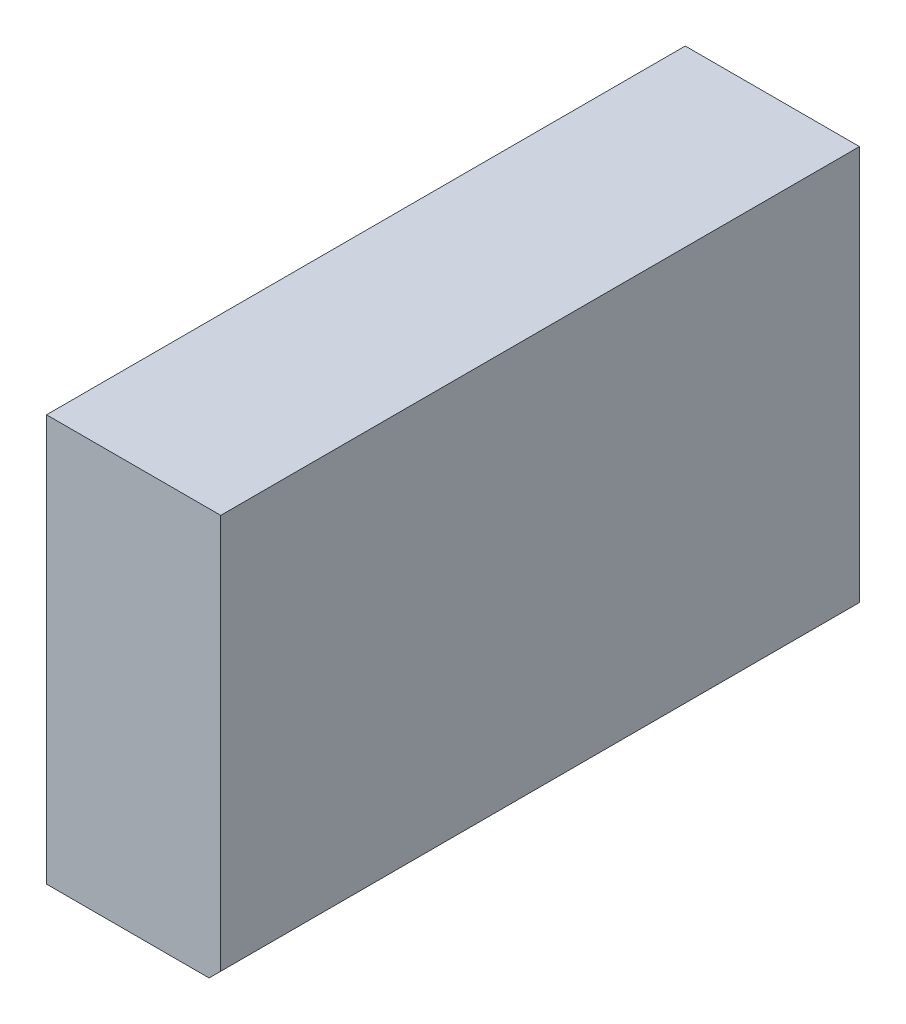
SolidWorks part; units mm, degrees
ref_plane "Front Plane" through (0, 0, 0) normal (0, 0, 1) x (1, 0, 0)
ref_plane "Top Plane" through (0, 0, 0) normal (0, 1, 0) x (1, 0, 0)
ref_plane "Right Plane" through (0, 0, 0) normal (1, 0, 0) x (0, 0, -1)
sketch "Sketch1" plane through (0, 0, 0) normal (0, 0, 1) x (1, 0, 0)
  line L1 (0, 0) -> (38.1, 0)
  line L2 (0, 0) -> (0, 88.9)
  line L3 (0, 88.9) -> (38.1, 88.9)
  line L4 (38.1, 0) -> (38.1, 88.9)
  dimension "D1" = 88.9
  dimension "D2" = 38.1
extrude "Boss-Extrude1" add sketch "Sketch1" along normal blind 139.7
chamfer "Chamfer1" distance 2.54 angle 45 1 edges at (38.1, 0, 69.85)
